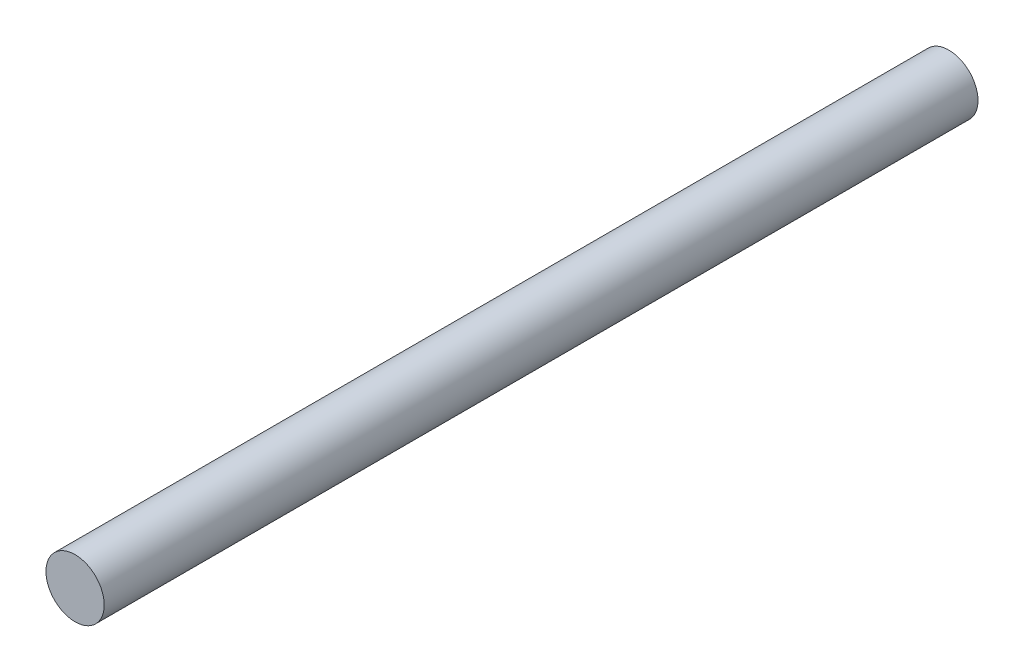
SolidWorks part; units mm, degrees
ref_plane "前视基准面" through (0, 0, 0) normal (0, 0, 1) x (1, 0, 0)
ref_plane "上视基准面" through (0, 0, 0) normal (0, 1, 0) x (1, 0, 0)
ref_plane "右视基准面" through (0, 0, 0) normal (1, 0, 0) x (0, 0, -1)
sketch "草图1" plane through (0, 0, 0) normal (0, 0, 1) x (1, 0, 0)
  circle A0 centre (0, 0) radius 0.5
  dimension "D1" = 1
extrude "凸台-拉伸1" add sketch "草图1" along normal blind 15
